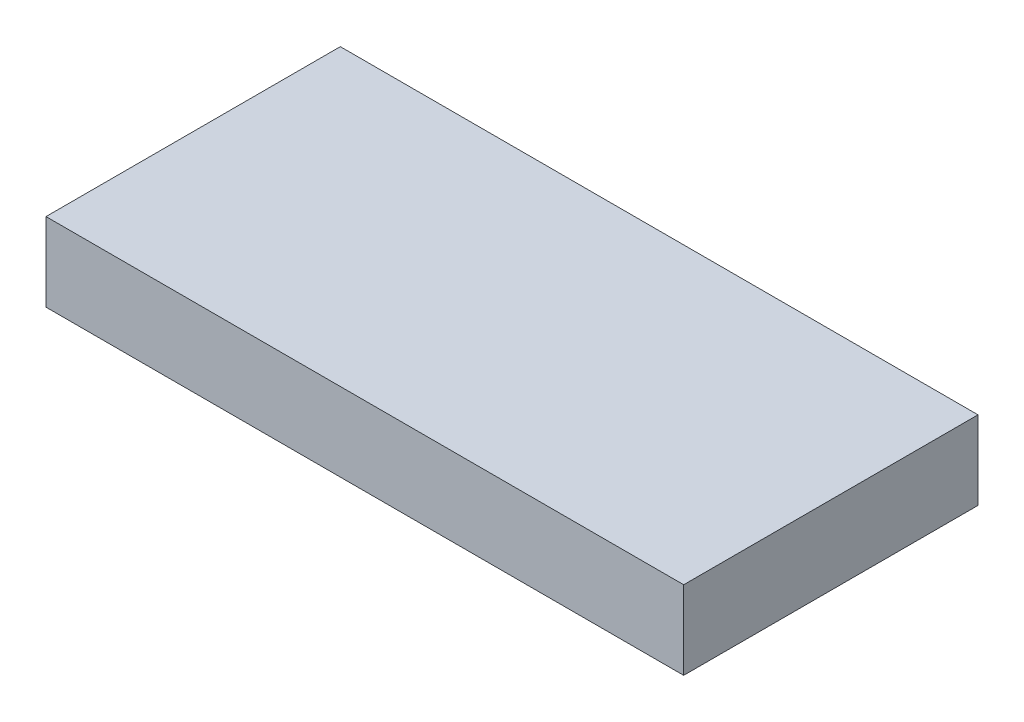
SolidWorks part; units mm, degrees
ref_plane "前视基准面" through (0, 0, 0) normal (0, 0, 1) x (1, 0, 0)
ref_plane "上视基准面" through (0, 0, 0) normal (0, 1, 0) x (1, 0, 0)
ref_plane "右视基准面" through (0, 0, 0) normal (1, 0, 0) x (0, 0, -1)
sketch "草图1" plane through (0, 0, 0) normal (0, 1, 0) x (1, 0, 0)
  line L1 (-32.5, 15) -> (32.5, 15)
  line L2 (-32.5, 15) -> (-32.5, -15)
  line L3 (-32.5, -15) -> (32.5, -15)
  line L4 (32.5, 15) -> (32.5, -15)
  line L5 (-32.5, 15) -> (32.5, -15) construction
  line L6 (-32.5, -15) -> (32.5, 15) construction
  point P0 (0, 0)
  dimension "D1" = 30
  dimension "D2" = 65
extrude "凸台-拉伸1" add sketch "草图1" along normal blind 8
